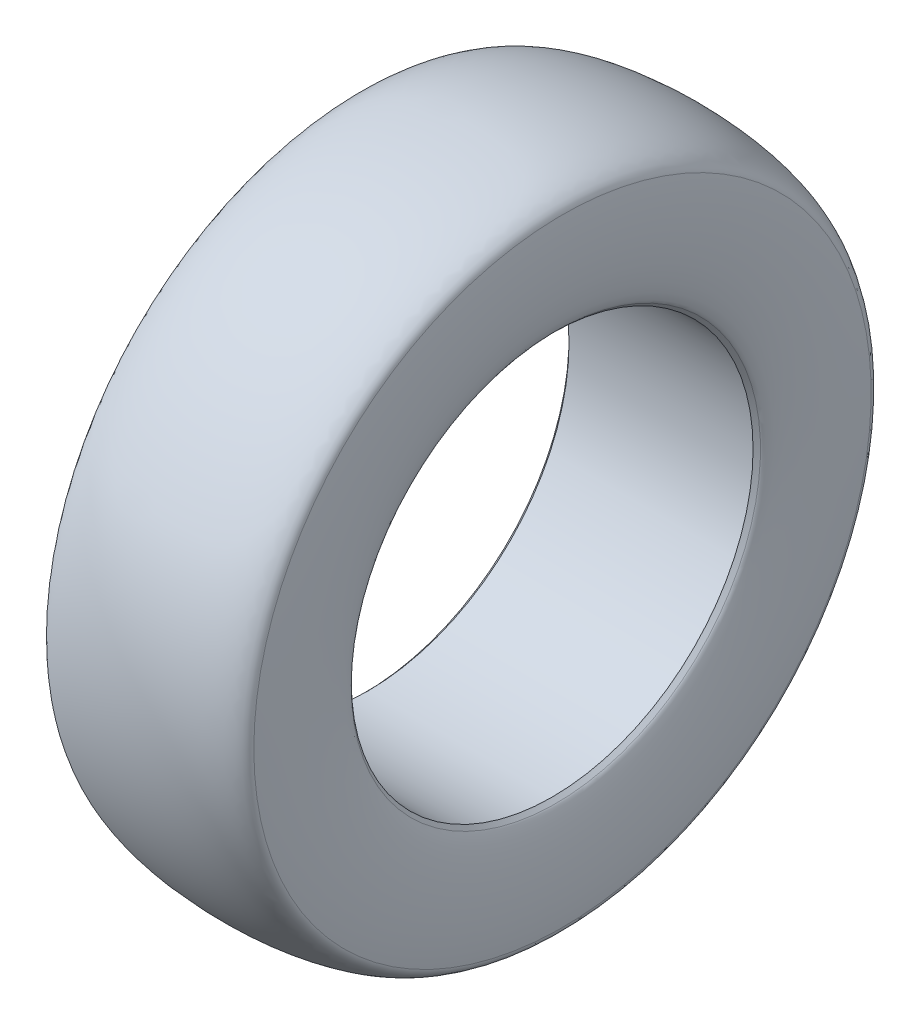
SolidWorks part; units mm, degrees
material "Rubber"
ref_plane "Front Plane" through (0, 0, 0) normal (0, 0, 1) x (1, 0, 0)
ref_plane "Top Plane" through (0, 0, 0) normal (0, 1, 0) x (1, 0, 0)
ref_plane "Right Plane" through (0, 0, 0) normal (1, 0, 0) x (0, 0, -1)
sketch "Sketch1" plane through (0, 0, 0) normal (0, 0, 1) x (1, 0, 0)
  line L0 (-1000, 0) -> (49000, 0) construction
  line L1 (-111.6697, 243.84) -> (111.6697, 243.84)
  line L2 (-127, 937.9425) -> (-127, -740.7419) construction
  line L3 (127, 852.2954) -> (127, -946.2951) construction
  line L4 (-682.5162, 406.4) -> (891.0312, 406.4) construction
  line L5 (-111.6697, 243.84) -> (-116.1599, 248.3301)
  line L6 (116.1599, 248.3301) -> (111.6697, 243.84)
  line L7 (0, 358.7485) -> (0, 466.2794) construction
  arc A0 (-116.1599, 248.3301) -> (-127, 243.84) centre (-120.65, 243.84) ccw construction
  arc A1 (127, 243.84) -> (116.1599, 248.3301) centre (120.65, 243.84) ccw construction
  ellipse E0 centre (-114.0568, 325.8863) end of major axis (-114.0568, 404.4869) minor radius 12.9432 (-124.217, 374.5807) -> (-116.1599, 248.3301) ccw
  ellipse E1 centre (0, 373.4459) end of major axis (-124.2907, 373.4459) minor radius 32.9541 (124.217, 374.5807) -> (-124.217, 374.5807) ccw
  ellipse E2 centre (114.0568, 325.8863) end of major axis (114.0568, 404.4869) minor radius 12.9432 (124.217, 374.5807) -> (116.1599, 248.3301) cw
  dimension "D4" = 12.7
  dimension "D2" = 254
  dimension "D3" = 406.4
revolve "Revolve2" add sketch "Sketch1" angle 360 about L0
